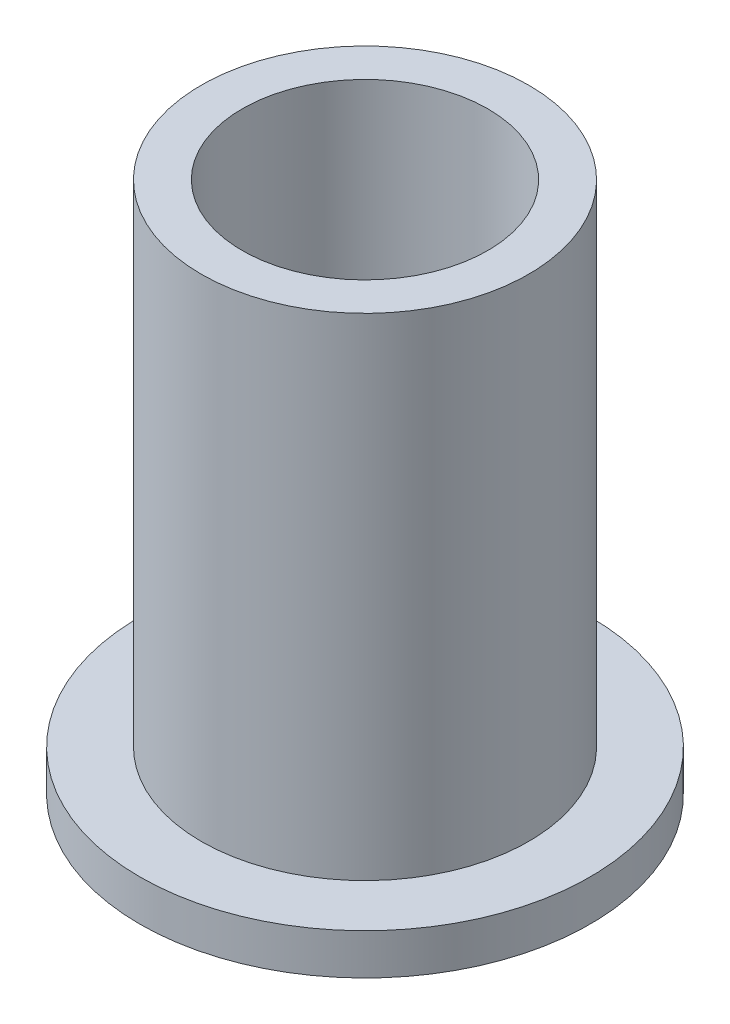
SolidWorks part; units mm, degrees
material "Brass"
ref_plane "Front Plane" through (0, 0, 0) normal (0, 0, 1) x (1, 0, 0)
ref_plane "Top Plane" through (0, 0, 0) normal (0, 1, 0) x (1, 0, 0)
ref_plane "Right Plane" through (0, 0, 0) normal (1, 0, 0) x (0, 0, -1)
sketch "Sketch1" plane through (0, 0, 0) normal (0, 0, 1) x (1, 0, 0)
  line L0 (0, 0) -> (0, 64.5027) construction
  line L1 (4.7625, 0) -> (4.7625, 20.6375)
  line L2 (4.7625, 20.6375) -> (6.35, 20.6375)
  line L3 (6.35, 20.6375) -> (6.35, 1.5875)
  line L4 (6.35, 1.5875) -> (8.7313, 1.5875)
  line L5 (8.7313, 1.5875) -> (8.7313, 0)
  line L6 (8.7313, 0) -> (4.7625, 0)
  dimension "D1" = 4.7625
  dimension "D2" = 6.35
  dimension "D3" = 8.7312
  dimension "D4" = 1.5875
  dimension "D5" = 19.05
revolve "Revolve1" add sketch "Sketch1" angle 360 about L0
equation "\"D1@Sketch1\"=3/16"
